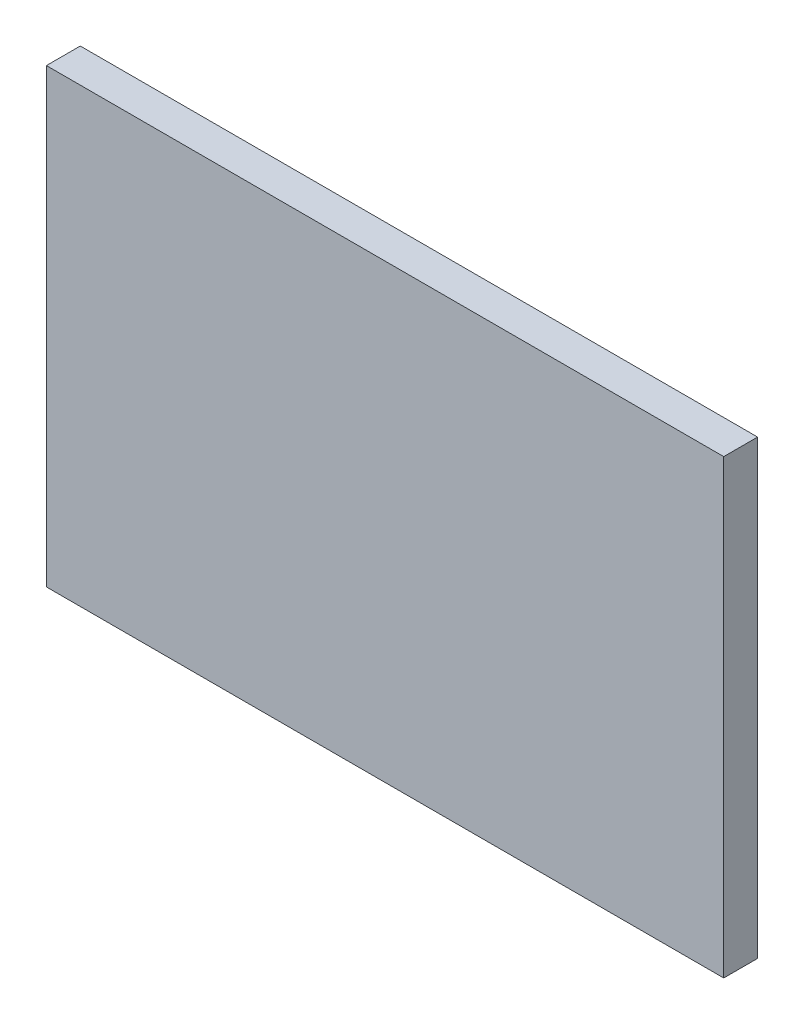
SolidWorks part; units mm, degrees
ref_plane "Front Plane" through (0, 0, 0) normal (0, 0, 1) x (1, 0, 0)
ref_plane "Top Plane" through (0, 0, 0) normal (0, 1, 0) x (1, 0, 0)
ref_plane "Right Plane" through (0, 0, 0) normal (1, 0, 0) x (0, 0, -1)
sketch "Sketch1" plane through (0, 0, 0) normal (0, 1, 0) x (1, 0, 0)
  line L1 (30, -1.5) -> (-30, -1.5)
  line L2 (30, -1.5) -> (30, 1.5)
  line L3 (30, 1.5) -> (-30, 1.5)
  line L4 (-30, -1.5) -> (-30, 1.5)
  line L5 (30, -1.5) -> (-30, 1.5) construction
  line L6 (30, 1.5) -> (-30, -1.5) construction
  point P0 (0, 0)
  dimension "D1" = 3
  dimension "D2" = 60
extrude "Boss-Extrude1" add sketch "Sketch1" along normal blind 40
